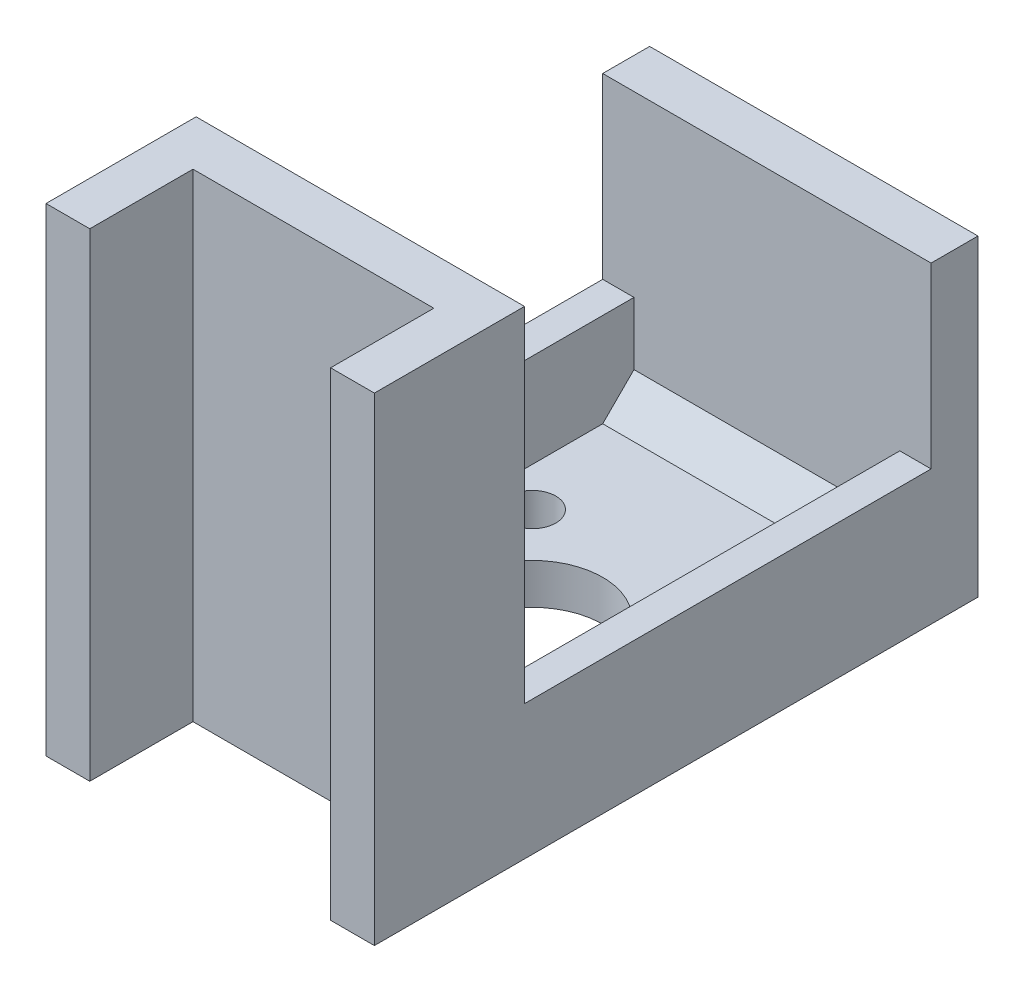
SolidWorks part; units mm, degrees
ref_plane "Front Plane" through (0, 0, 0) normal (0, 0, 1) x (1, 0, 0)
ref_plane "Top Plane" through (0, 0, 0) normal (0, 1, 0) x (1, 0, 0)
ref_plane "Right Plane" through (0, 0, 0) normal (1, 0, 0) x (0, 0, -1)
sketch "Sketch1" plane through (0, 0, 0) normal (0, 1, 0) x (1, 0, 0)
  line L0 (-3, -3) -> (3, 3) construction
  line L1 (-5.25, 7) -> (5.25, 7)
  line L2 (-5.25, 7) -> (-5.25, -7)
  line L3 (-5.25, -7) -> (5.25, -7)
  line L4 (5.25, 7) -> (5.25, -7)
  line L5 (-5.25, 7) -> (5.25, -7) construction
  line L6 (-5.25, -7) -> (5.25, 7) construction
  circle A0 centre (-3, 3) radius 0.75
  circle A1 centre (3, 3) radius 0.75
  circle A2 centre (-3, -3) radius 0.75
  circle A3 centre (3, -3) radius 0.75
  circle A4 centre (0, 0) radius 2.25
  point P0 (0, 0)
  point P14 (0, 0)
  point P15 (0, 0)
  point P16 (0, 0)
  dimension "D1" = 1.5
  dimension "D4" = 4.5
  dimension "D2" = 6
  dimension "D3" = 14
  dimension "D5" = 10.5
  dimension "D6" = 6
extrude "Boss-Extrude1" add sketch "Sketch1" along normal blind 1.3
sketch "Sketch2" plane through (0, 1.3, 0) normal (0, 1, 0) x (1, 0, 0)
  line L1 (-5.25, -7) -> (5.25, -7)
  line L3 (-5.25, -5.5) -> (5.25, -5.5)
  line L5 (-5.25, -7) -> (-5.25, -5.5)
  line L6 (5.25, -5.5) -> (5.25, -7)
  line L7 (-5.25, -7) -> (5.25, -7) construction
  point P1 (0, -5.5)
  point P3 (0, 0)
  dimension "D1" = 1.5
  dimension "D2" = 10.5
extrude "Boss-Extrude2" add sketch "Sketch2" along normal blind 14
sketch "Sketch3" plane through (0, 0, 0) normal (0, -1, 0) x (1, 0, 0)
  line L0 (-5.25, 7) -> (5.25, 7) construction
  line L1 (-5.25, 7) -> (-3.85, 7)
  line L2 (-5.25, 7) -> (-5.25, 10.3)
  line L3 (-5.25, 10.3) -> (-3.85, 10.3)
  line L4 (-3.85, 7) -> (-3.85, 10.3)
  line L5 (-3.85, 10.3) -> (3.85, 10.3) construction
  line L6 (5.25, 7) -> (3.85, 7)
  line L7 (5.25, 7) -> (5.25, 10.3)
  line L8 (5.25, 10.3) -> (3.85, 10.3)
  line L9 (3.85, 7) -> (3.85, 10.3)
  line L10 (-5.25, -7) -> (-5.25, 7) construction
  line L11 (5.25, 7) -> (5.25, -7) construction
  dimension "D1" = 1.4
  dimension "D2" = 3.3
extrude "Boss-Extrude3" add sketch "Sketch3" against normal up to surface (15.3 mm away) up to face at (0, 15.3, 6.25)
sketch "Sketch4" plane through (0, 0, 0) normal (0, -1, 0) x (1, 0, 0)
  line L0 (5.25, 10.3) -> (5.25, -7) construction
  line L1 (-5.25, -7) -> (5.25, -7)
  line L2 (-5.25, -7) -> (-5.25, -7.5)
  line L3 (-5.25, -7.5) -> (5.25, -7.5)
  line L4 (5.25, -7) -> (5.25, -7.5)
  dimension "D1" = 7.5
extrude "Boss-Extrude4" add sketch "Sketch4" against normal up to surface (1.3 mm away) up to face at (0, 1.3, -0.75)
sketch "Sketch5" plane through (0, 0, 0) normal (0, -1, 0) x (1, 0, 0)
  line L0 (5.25, 10.3) -> (5.25, -7.5) construction
  line L1 (-5.25, -7.5) -> (5.25, -7.5)
  line L2 (-5.25, -7.5) -> (-5.25, -9)
  line L3 (-5.25, -9) -> (5.25, -9)
  line L4 (5.25, -7.5) -> (5.25, -9)
  dimension "D1" = 1.5
extrude "Boss-Extrude5" add sketch "Sketch5" against normal blind 10
sketch "Sketch6" plane through (0, 1.3, 0) normal (0, 1, 0) x (1, 0, 0)
  line L0 (-5.25, 7.5) -> (5.25, 7.5) construction
  line L1 (5.25, -5.5) -> (4.25, -5.5)
  line L2 (5.25, -5.5) -> (5.25, 7.5)
  line L3 (5.25, 7.5) -> (4.25, 7.5)
  line L4 (4.25, -5.5) -> (4.25, 7.5)
  line L5 (-5.25, -5.5) -> (-4.25, -5.5)
  line L6 (-5.25, -5.5) -> (-5.25, 7.5)
  line L7 (-5.25, 7.5) -> (-4.25, 7.5)
  line L8 (-4.25, -5.5) -> (-4.25, 7.5)
  dimension "D1" = 1
extrude "Boss-Extrude6" add sketch "Sketch6" along normal blind 3
chamfer "Chamfer1" distance 1 angle 45 1 edges at (0, 1.3, -7.5)
